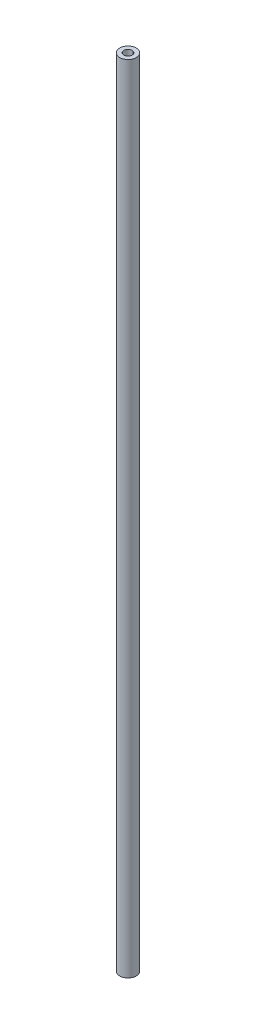
SolidWorks part; units mm, degrees
ref_plane "Front Plane" through (0, 0, 0) normal (0, 0, 1) x (1, 0, 0)
ref_plane "Top Plane" through (0, 0, 0) normal (0, 1, 0) x (1, 0, 0)
ref_plane "Right Plane" through (0, 0, 0) normal (1, 0, 0) x (0, 0, -1)
sketch "Sketch1" plane through (0, 0, 0) normal (0, 1, 0) x (1, 0, 0)
  circle A0 centre (0, 0) radius 6.35
  dimension "D1" = 12.7
extrude "Boss-Extrude1" add sketch "Sketch1" along normal blind 609.6
sketch "Sketch2" plane through (0, 609.6, 0) normal (0, 1, 0) x (1, 0, 0)
  circle A0 centre (0, 0) radius 3.175
  dimension "D1" = 6.35
extrude "Cut-Extrude1" cut sketch "Sketch2" against normal up to next
